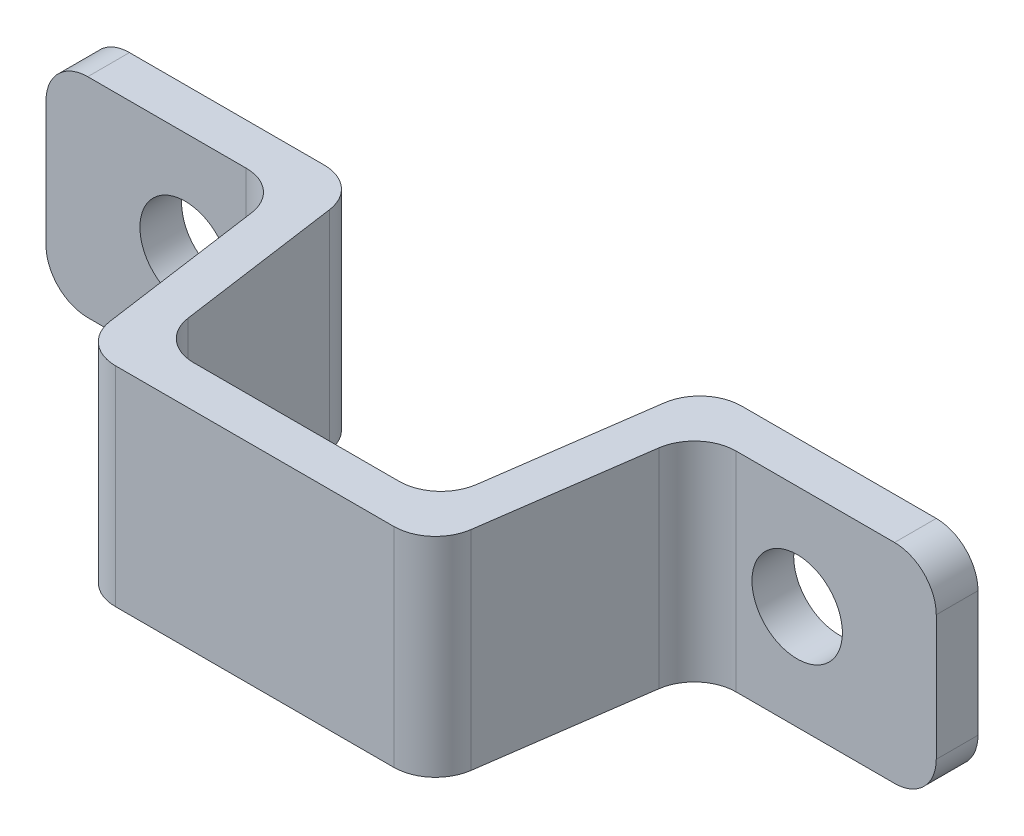
SolidWorks part; units mm, degrees
ref_plane "前视基准面" through (0, 0, 0) normal (0, 0, 1) x (1, 0, 0)
ref_plane "上视基准面" through (0, 0, 0) normal (0, 1, 0) x (1, 0, 0)
ref_plane "右视基准面" through (0, 0, 0) normal (1, 0, 0) x (0, 0, -1)
other "Configuration Table"
sketch "草图1" plane through (0, 0, 0) normal (0, 1, 0) x (1, 0, 0)
  line L0 (-12.6073, 0) -> (12.6073, 0)
  line L1 (12.6073, 0) -> (15, 17)
  line L2 (15, 17) -> (32, 17)
  line L3 (32, 17) -> (32, 20)
  line L4 (32, 20) -> (12.3927, 20)
  line L5 (12.3927, 20) -> (10, 3)
  line L6 (0, 0) -> (0, 19.9061) construction
  line L7 (-12.3927, 20) -> (-10, 3)
  line L8 (-32, 20) -> (-12.3927, 20)
  line L9 (-32, 17) -> (-32, 20)
  line L10 (-15, 17) -> (-32, 17)
  line L11 (-12.6073, 0) -> (-15, 17)
  line L12 (-10, 3) -> (10, 3)
  point P4 (0, 0)
  point P17 (11.7164, 6.2993)
  point P18 (17, 13.8181)
  dimension "D1" = 64
  dimension "D2" = 17
  dimension "D3" = 3
  dimension "D4" = 3
  dimension "D5" = 20
  dimension "D6" = 3
  dimension "D7" = 20
extrude "凸台-拉伸1" add sketch "草图1" along normal mid plane 15
sketch "草图2" plane through (0, 0, -17) normal (0, 0, 1) x (1, 0, 0)
  line L0 (32, 0) -> (-32, 0) construction
  line L1 (32, 7.5) -> (32, -7.5) construction
  line L2 (-32, 7.5) -> (-32, -7.5) construction
  line L3 (0, 0) -> (0, 7.5) construction
  line L4 (-12.6073, 7.5) -> (12.6073, 7.5) construction
  circle A0 centre (-22, 0) radius 3.25
  circle A1 centre (22, 0) radius 3.25
  dimension "D1" = 6.5
  dimension "D2" = 10
extrude "切除-拉伸1" cut sketch "草图2" against normal through all
fillet "圆角1" radius 3 8 edges at (-12.3927, 0, -20) (12.3927, 0, -20) (10, 0, -3) (-10, 0, -3) (15, 0, -17) (12.6073, 0, 0) (-12.6073, 0, 0) (-15, 0, -17)
fillet "圆角2" radius 3 4 edges at (32, -7.5, -18.5) (32, 7.5, -18.5) (-32, -7.5, -18.5) (-32, 7.5, -18.5)
